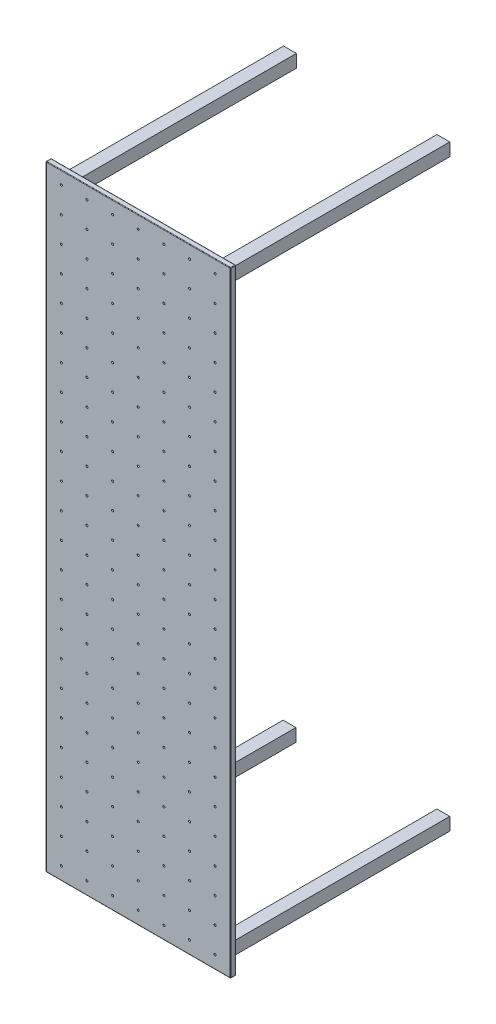
SolidWorks part; units mm, degrees
ref_plane "Front Plane" through (0, 0, 0) normal (0, 0, 1) x (1, 0, 0)
ref_plane "Top Plane" through (0, 0, 0) normal (0, 1, 0) x (1, 0, 0)
ref_plane "Right Plane" through (0, 0, 0) normal (1, 0, 0) x (0, 0, -1)
sketch "Sketch1" plane through (0, 0, 0) normal (0, 0, 1) x (1, 0, 0)
  line L0 (0, 0) -> (-179871.7364, 0) construction
  line L1 (0, 0) -> (0, 179871.7364) construction
  line L3 (360, -1200) -> (-360, -1200)
  line L4 (360, -1200) -> (360, 1200)
  line L5 (360, 1200) -> (-360, 1200)
  line L6 (-360, -1200) -> (-360, 1200)
  line L7 (360, -1200) -> (-360, 1200) construction
  line L8 (360, 1200) -> (-360, -1200) construction
  point P5 (0, 0)
  dimension "D1" = 720
  dimension "D2" = 2400
extrude "Boss-Extrude1" add sketch "Sketch1" along normal blind 20
sketch "Sketch2" plane through (0, 0, 20) normal (0, 0, 1) x (1, 0, 0)
  line L0 (360, 1200) -> (-360, 1200) construction
  line L1 (-360, 1200) -> (-360, -1200) construction
  circle A0 centre (-300, 1150) radius 4
  circle A1 centre (-200, 1150) radius 4
  circle A2 centre (-100, 1150) radius 4
  circle A3 centre (0, 1150) radius 4
  circle A4 centre (100, 1150) radius 4
  circle A5 centre (200, 1150) radius 4
  circle A6 centre (300, 1150) radius 4
  circle A7 centre (-200, 1050) radius 4
  circle A8 centre (-100, 1050) radius 4
  circle A9 centre (0, 1050) radius 4
  circle A10 centre (100, 1050) radius 4
  circle A11 centre (200, 1050) radius 4
  circle A12 centre (300, 1050) radius 4
  circle A13 centre (-200, 950) radius 4
  circle A14 centre (-100, 950) radius 4
  circle A15 centre (0, 950) radius 4
  circle A16 centre (100, 950) radius 4
  circle A17 centre (200, 950) radius 4
  circle A18 centre (300, 950) radius 4
  circle A19 centre (-200, 850) radius 4
  circle A20 centre (-100, 850) radius 4
  circle A21 centre (0, 850) radius 4
  circle A22 centre (100, 850) radius 4
  circle A23 centre (200, 850) radius 4
  circle A24 centre (300, 850) radius 4
  circle A25 centre (-200, 750) radius 4
  circle A26 centre (-100, 750) radius 4
  circle A27 centre (0, 750) radius 4
  circle A28 centre (100, 750) radius 4
  circle A29 centre (200, 750) radius 4
  circle A30 centre (300, 750) radius 4
  circle A31 centre (-300, 1050) radius 4
  circle A32 centre (-300, 950) radius 4
  circle A33 centre (-300, 850) radius 4
  circle A34 centre (-300, 750) radius 4
  circle A35 centre (-300, 1050) radius 4
  circle A36 centre (-300, 950) radius 4
  circle A37 centre (-300, 850) radius 4
  circle A38 centre (-300, 750) radius 4
  circle A39 centre (-300, 650) radius 4
  circle A40 centre (-300, 550) radius 4
  circle A41 centre (-300, 450) radius 4
  circle A42 centre (-300, 350) radius 4
  circle A43 centre (-300, 250) radius 4
  circle A44 centre (-300, 150) radius 4
  circle A45 centre (-300, 50) radius 4
  circle A46 centre (-300, -50) radius 4
  circle A47 centre (-300, -150) radius 4
  circle A48 centre (-300, -250) radius 4
  circle A49 centre (-300, -350) radius 4
  circle A50 centre (-300, -450) radius 4
  circle A51 centre (-300, -550) radius 4
  circle A52 centre (-300, -650) radius 4
  circle A53 centre (-300, -750) radius 4
  circle A54 centre (-300, -850) radius 4
  circle A55 centre (-300, -950) radius 4
  circle A56 centre (-300, -1050) radius 4
  circle A57 centre (-300, -1150) radius 4
  circle A58 centre (-200, 1050) radius 4
  circle A59 centre (-200, 950) radius 4
  circle A60 centre (-200, 850) radius 4
  circle A61 centre (-200, 750) radius 4
  circle A62 centre (-200, 650) radius 4
  circle A63 centre (-200, 550) radius 4
  circle A64 centre (-200, 450) radius 4
  circle A65 centre (-200, 350) radius 4
  circle A66 centre (-200, 250) radius 4
  circle A67 centre (-200, 150) radius 4
  circle A68 centre (-200, 50) radius 4
  circle A69 centre (-200, -50) radius 4
  circle A70 centre (-200, -150) radius 4
  circle A71 centre (-200, -250) radius 4
  circle A72 centre (-200, -350) radius 4
  circle A73 centre (-200, -450) radius 4
  circle A74 centre (-200, -550) radius 4
  circle A75 centre (-200, -650) radius 4
  circle A76 centre (-200, -750) radius 4
  circle A77 centre (-200, -850) radius 4
  circle A78 centre (-200, -950) radius 4
  circle A79 centre (-200, -1050) radius 4
  circle A80 centre (-200, -1150) radius 4
  circle A81 centre (-100, 1050) radius 4
  circle A82 centre (-100, 950) radius 4
  circle A83 centre (-100, 850) radius 4
  circle A84 centre (-100, 750) radius 4
  circle A85 centre (-100, 650) radius 4
  circle A86 centre (-100, 550) radius 4
  circle A87 centre (-100, 450) radius 4
  circle A88 centre (-100, 350) radius 4
  circle A89 centre (-100, 250) radius 4
  circle A90 centre (-100, 150) radius 4
  circle A91 centre (-100, 50) radius 4
  circle A92 centre (-100, -50) radius 4
  circle A93 centre (-100, -150) radius 4
  circle A94 centre (-100, -250) radius 4
  circle A95 centre (-100, -350) radius 4
  circle A96 centre (-100, -450) radius 4
  circle A97 centre (-100, -550) radius 4
  circle A98 centre (-100, -650) radius 4
  circle A99 centre (-100, -750) radius 4
  circle A100 centre (-100, -850) radius 4
  circle A101 centre (-100, -950) radius 4
  circle A102 centre (-100, -1050) radius 4
  circle A103 centre (-100, -1150) radius 4
  circle A104 centre (0, 1050) radius 4
  circle A105 centre (0, 950) radius 4
  circle A106 centre (0, 850) radius 4
  circle A107 centre (0, 750) radius 4
  circle A108 centre (0, 650) radius 4
  circle A109 centre (0, 550) radius 4
  circle A110 centre (0, 450) radius 4
  circle A111 centre (0, 350) radius 4
  circle A112 centre (0, 250) radius 4
  circle A113 centre (0, 150) radius 4
  circle A114 centre (0, 50) radius 4
  circle A115 centre (0, -50) radius 4
  circle A116 centre (0, -150) radius 4
  circle A117 centre (0, -250) radius 4
  circle A118 centre (0, -350) radius 4
  circle A119 centre (0, -450) radius 4
  circle A120 centre (0, -550) radius 4
  circle A121 centre (0, -650) radius 4
  circle A122 centre (0, -750) radius 4
  circle A123 centre (0, -850) radius 4
  circle A124 centre (0, -950) radius 4
  circle A125 centre (0, -1050) radius 4
  circle A126 centre (0, -1150) radius 4
  circle A127 centre (100, 1050) radius 4
  circle A128 centre (100, 950) radius 4
  circle A129 centre (100, 850) radius 4
  circle A130 centre (100, 750) radius 4
  circle A131 centre (100, 650) radius 4
  circle A132 centre (100, 550) radius 4
  circle A133 centre (100, 450) radius 4
  circle A134 centre (100, 350) radius 4
  circle A135 centre (100, 250) radius 4
  circle A136 centre (100, 150) radius 4
  circle A137 centre (100, 50) radius 4
  circle A138 centre (100, -50) radius 4
  circle A139 centre (100, -150) radius 4
  circle A140 centre (100, -250) radius 4
  circle A141 centre (100, -350) radius 4
  circle A142 centre (100, -450) radius 4
  circle A143 centre (100, -550) radius 4
  circle A144 centre (100, -650) radius 4
  circle A145 centre (100, -750) radius 4
  circle A146 centre (100, -850) radius 4
  circle A147 centre (100, -950) radius 4
  circle A148 centre (100, -1050) radius 4
  circle A149 centre (100, -1150) radius 4
  circle A150 centre (200, 1050) radius 4
  circle A151 centre (200, 950) radius 4
  circle A152 centre (200, 850) radius 4
  circle A153 centre (200, 750) radius 4
  circle A154 centre (200, 650) radius 4
  circle A155 centre (200, 550) radius 4
  circle A156 centre (200, 450) radius 4
  circle A157 centre (200, 350) radius 4
  circle A158 centre (200, 250) radius 4
  circle A159 centre (200, 150) radius 4
  circle A160 centre (200, 50) radius 4
  circle A161 centre (200, -50) radius 4
  circle A162 centre (200, -150) radius 4
  circle A163 centre (200, -250) radius 4
  circle A164 centre (200, -350) radius 4
  circle A165 centre (200, -450) radius 4
  circle A166 centre (200, -550) radius 4
  circle A167 centre (200, -650) radius 4
  circle A168 centre (200, -750) radius 4
  circle A169 centre (200, -850) radius 4
  circle A170 centre (200, -950) radius 4
  circle A171 centre (200, -1050) radius 4
  circle A172 centre (200, -1150) radius 4
  circle A173 centre (300, 1050) radius 4
  circle A174 centre (300, 950) radius 4
  circle A175 centre (300, 850) radius 4
  circle A176 centre (300, 750) radius 4
  circle A177 centre (300, 650) radius 4
  circle A178 centre (300, 550) radius 4
  circle A179 centre (300, 450) radius 4
  circle A180 centre (300, 350) radius 4
  circle A181 centre (300, 250) radius 4
  circle A182 centre (300, 150) radius 4
  circle A183 centre (300, 50) radius 4
  circle A184 centre (300, -50) radius 4
  circle A185 centre (300, -150) radius 4
  circle A186 centre (300, -250) radius 4
  circle A187 centre (300, -350) radius 4
  circle A188 centre (300, -450) radius 4
  circle A189 centre (300, -550) radius 4
  circle A190 centre (300, -650) radius 4
  circle A191 centre (300, -750) radius 4
  circle A192 centre (300, -850) radius 4
  circle A193 centre (300, -950) radius 4
  circle A194 centre (300, -1050) radius 4
  circle A195 centre (300, -1150) radius 4
  circle A196 centre (-200, 1150) radius 4
  circle A197 centre (-100, 1150) radius 4
  circle A198 centre (0, 1150) radius 4
  circle A199 centre (100, 1150) radius 4
  circle A200 centre (200, 1150) radius 4
  circle A201 centre (300, 1150) radius 4
  dimension "D1" = 8
  dimension "D2" = 50
  dimension "D3" = 60
  dimension "D4" = 7
  dimension "D5" = 5
  dimension "D6" = 24
  dimension "D7" = 7
extrude "Cut-Extrude1" cut sketch "Sketch2" against normal blind 10
fillet "Fillet1" radius 2 12 edges at (-360, 1200, 10) (0, 1200, 0) (0, 1200, 20) (360, 1200, 10) (360, 0, 0) (360, 0, 20) (360, -1200, 10) (-360, 0, 0) (0, -1200, 0) (-360, 0, 20) (0, -1200, 20) (-360, -1200, 10)
sketch "Sketch3" plane through (0, 0, 0) normal (0, 0, -1) x (-1, 0, 0)
  line L0 (358, 1198) -> (-358, 1198) construction
  line L1 (-325, 1163) -> (-275, 1163)
  line L2 (-325, 1163) -> (-325, 1113)
  line L3 (-325, 1113) -> (-275, 1113)
  line L4 (-275, 1163) -> (-275, 1113)
  line L5 (-325, 1163) -> (-275, 1113) construction
  line L6 (-325, 1113) -> (-275, 1163) construction
  line L7 (273, 1163) -> (323, 1163)
  line L8 (273, 1163) -> (273, 1113)
  line L9 (273, 1113) -> (323, 1113)
  line L10 (323, 1163) -> (323, 1113)
  line L11 (273, 1163) -> (323, 1113) construction
  line L12 (273, 1113) -> (323, 1163) construction
  line L13 (275, -1115) -> (325, -1115)
  line L14 (275, -1115) -> (275, -1165)
  line L15 (275, -1165) -> (325, -1165)
  line L16 (325, -1115) -> (325, -1165)
  line L17 (275, -1115) -> (325, -1165) construction
  line L18 (275, -1165) -> (325, -1115) construction
  line L19 (-325, -1115) -> (-275, -1115)
  line L20 (-325, -1115) -> (-325, -1165)
  line L21 (-325, -1165) -> (-275, -1165)
  line L22 (-275, -1115) -> (-275, -1165)
  line L23 (-325, -1115) -> (-275, -1165) construction
  line L24 (-325, -1165) -> (-275, -1115) construction
  line L25 (358, -1198) -> (358, 1198) construction
  line L26 (-360, -1198) -> (-360, 1198) construction
  line L27 (358, -1200) -> (-358, -1200) construction
  line L28 (360, 1198) -> (360, -1198) construction
  point P0 (-300, 1138)
  point P5 (298, 1138)
  point P10 (300, -1140)
  point P15 (-300, -1140)
  dimension "D1" = 50
  dimension "D2" = 50
  dimension "D3" = 50
  dimension "D4" = 50
  dimension "D5" = 50
  dimension "D6" = 50
  dimension "D7" = 50
  dimension "D8" = 60
  dimension "D9" = 60
  dimension "D10" = 60
  dimension "D11" = 60
  dimension "D12" = 60
  dimension "D13" = 60
  dimension "D14" = 60
  dimension "D15" = 60
extrude "Boss-Extrude2" add sketch "Sketch3" along normal blind 870
